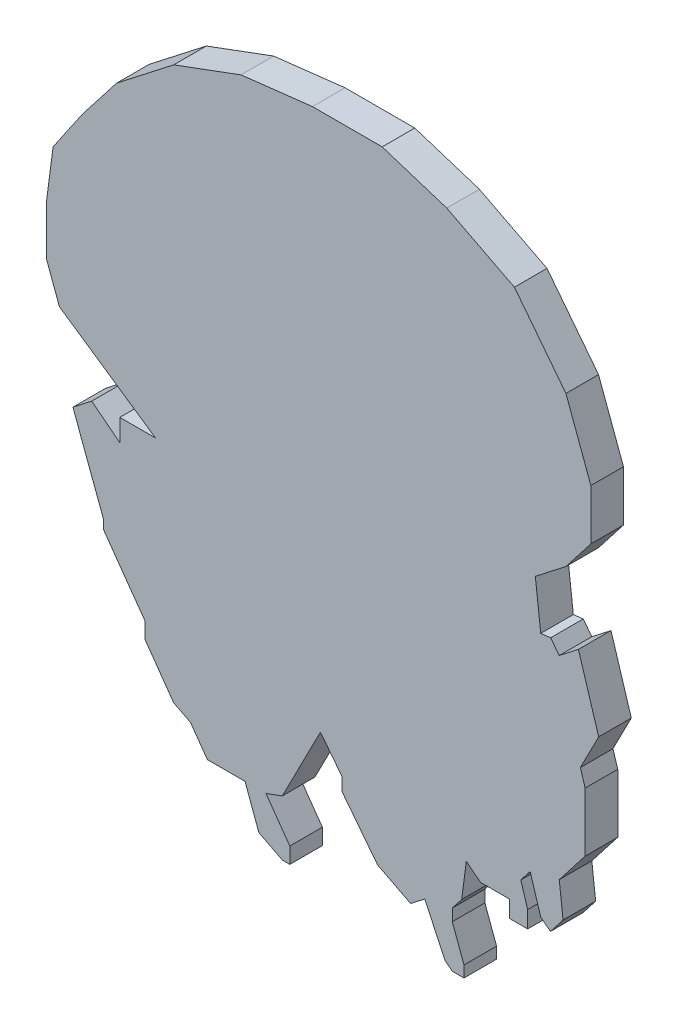
SolidWorks part; units mm, degrees
ref_plane "Спереди" through (0, 0, 0) normal (0, 0, 1) x (1, 0, 0)
ref_plane "Сверху" through (0, 0, 0) normal (0, 1, 0) x (1, 0, 0)
ref_plane "Справа" through (0, 0, 0) normal (1, 0, 0) x (0, 0, -1)
sketch "Эскиз1" plane through (0, 0, 0) normal (0, 0, 1) x (1, 0, 0)
  line L0 (-105.2933, 622.2185) -> (701.4087, 622.2185) construction
  line L5 (-53.8514, 14.0186) -> (-57.0454, 22.6425)
  line L6 (-57.0454, 22.6425) -> (-51.2962, 27.1141)
  line L7 (-51.2962, 27.1141) -> (-42.6723, 20.4066)
  line L8 (-42.6723, 20.4066) -> (-42.6723, 27.1141)
  line L9 (-42.6723, 27.1141) -> (-31.7327, 27.1141)
  line L10 (-31.7327, 27.1141) -> (-61.1977, 47.2365)
  line L11 (-61.1977, 47.2365) -> (-65.0929, 57.7537)
  line L12 (-65.0929, 57.7537) -> (-65.0929, 73.747)
  line L13 (-65.0929, 73.747) -> (-63.1453, 88.7589)
  line L14 (-63.1453, 88.7589) -> (-54.1708, 101.9001)
  line L15 (-54.1708, 101.9001) -> (-43.6674, 115.4045)
  line L16 (-43.6674, 115.4045) -> (-26.1304, 129.0444)
  line L17 (-26.1304, 129.0444) -> (-5.4664, 136.6977)
  line L18 (-5.4664, 136.6977) -> (16.4173, 139.2246)
  line L19 (16.4173, 139.2246) -> (37.8173, 139.2246)
  line L20 (37.8173, 139.2246) -> (57.6203, 132.871)
  line L21 (57.6203, 132.871) -> (78.3815, 122.2244)
  line L22 (78.3815, 122.2244) -> (94.1893, 101.9001)
  line L23 (94.1893, 101.9001) -> (101.8364, 81.2529)
  line L24 (101.8364, 81.2529) -> (101.8364, 65.7503)
  line L25 (101.8364, 65.7503) -> (94.1893, 55.9183)
  line L26 (94.1893, 55.9183) -> (84.7982, 48.6142)
  line L27 (84.7982, 48.6142) -> (86.4527, 34.2859)
  line L28 (86.4527, 34.2859) -> (89.4938, 34.6371)
  line L29 (89.4938, 34.6371) -> (92.1328, 31.244)
  line L30 (92.1328, 31.244) -> (98.0128, 35.8174)
  line L31 (98.0128, 35.8174) -> (104.2339, 15.6855)
  line L32 (104.2339, 15.6855) -> (98.6194, 4.737)
  line L33 (98.6194, 4.737) -> (100.0832, 0)
  line L34 (100.0832, 0) -> (100.0832, -10.3266)
  line L35 (100.0832, -10.3266) -> (100.0832, -18.0752)
  line L36 (100.0832, -18.0752) -> (92.1328, -28.2972)
  line L37 (92.1328, -28.2972) -> (93.3038, -38.4383)
  line L38 (93.3038, -38.4383) -> (89.4369, -43.41)
  line L39 (89.4369, -43.41) -> (86.4527, -41.089)
  line L40 (86.4527, -41.089) -> (83.2069, -30.5851)
  line L41 (83.2069, -30.5851) -> (80.3387, -34.2728)
  line L42 (80.3387, -34.2728) -> (82.445, -41.089)
  line L43 (82.445, -41.089) -> (82.445, -46.2417)
  line L44 (82.445, -46.2417) -> (76.9123, -46.2417)
  line L45 (76.9123, -46.2417) -> (76.9123, -41.089)
  line L46 (76.9123, -41.089) -> (68.0009, -41.089)
  line L47 (68.0009, -41.089) -> (63.6191, -37.6809)
  line L48 (63.6191, -37.6809) -> (62.2111, -48.5329)
  line L49 (62.2111, -48.5329) -> (59.3246, -52.2442)
  line L50 (59.3246, -52.2442) -> (59.3246, -55.8828)
  line L51 (59.3246, -55.8828) -> (62.9151, -65.5771)
  line L52 (62.9151, -65.5771) -> (62.9151, -69.0387)
  line L53 (62.9151, -69.0387) -> (59.3246, -69.0387)
  line L54 (59.3246, -69.0387) -> (57.0993, -67.3079)
  line L55 (57.0993, -67.3079) -> (50.877, -54.0635)
  line L56 (50.877, -54.0635) -> (46.5321, -57.4429)
  line L57 (46.5321, -57.4429) -> (36.3945, -52.2442)
  line L58 (36.3945, -52.2442) -> (25.5136, -38.2545)
  line L59 (25.5136, -38.2545) -> (25.5136, -34.2728)
  line L60 (25.5136, -34.2728) -> (18.8734, -25.7354)
  line L61 (18.8734, -25.7354) -> (14.4954, -34.2728)
  line L62 (14.4954, -34.2728) -> (8.8665, -45.2493)
  line L63 (8.8665, -45.2493) -> (7.1826, -48.5329)
  line L64 (7.1826, -48.5329) -> (2.1725, -50.3886)
  line L65 (2.1725, -50.3886) -> (7.1826, -57.4429)
  line L66 (7.1826, -57.4429) -> (9.4857, -60.6857)
  line L67 (9.4857, -60.6857) -> (9.4857, -65.5771)
  line L68 (9.4857, -65.5771) -> (7.1826, -65.5771)
  line L69 (7.1826, -65.5771) -> (0, -61.8937)
  line L70 (0, -61.8937) -> (-1.6485, -57.4429)
  line L71 (-1.6485, -57.4429) -> (-4.2612, -50.3886)
  line L72 (-4.2612, -50.3886) -> (-7.1994, -50.3886)
  line L73 (-7.1994, -50.3886) -> (-12.0971, -50.3886)
  line L74 (-12.0971, -50.3886) -> (-15.7984, -50.3886)
  line L75 (-15.7984, -50.3886) -> (-20.97, -43.1069)
  line L76 (-20.97, -43.1069) -> (-26.1304, -40.4606)
  line L77 (-26.1304, -40.4606) -> (-29.1112, -36.2636)
  line L78 (-29.1112, -36.2636) -> (-34.8989, -28.1146)
  line L79 (-34.8989, -28.1146) -> (-34.8989, -23.1862)
  line L80 (-34.8989, -23.1862) -> (-37.2025, -19.9427)
  line L81 (-37.2025, -19.9427) -> (-47.6992, -5.1633)
  line L82 (-47.6992, -5.1633) -> (-47.6992, -2.3786)
  line L83 (-47.6992, -2.3786) -> (-53.8514, 14.0186)
  point P85 (-205.7009, -120.4925)
extrude "Бобышка-Вытянуть1" add sketch "Эскиз1" along normal blind 10 contours L83 L5 L6 L7 L8 L9 L10 L11 L12 L13 L14 L15 L16 L17 L18 L19 L20 L21 L22 L23 L24 L25 L26 L27 L28 L29 L30 L31 L32 L33 L34 L35 L36 L37 L38 L39 L40 L41 L42 L43 L44 L45 L46 L47 L48 L49 L50 L51 L52 L53 L54 L55 L56 L57 L58 L59 L60 L61 L62 L63 L64 L65 L66 L67 L68 L69 L70 L71 L72 L73 L74 L75 L76 L77 L78 L79 L80 L81 L82
